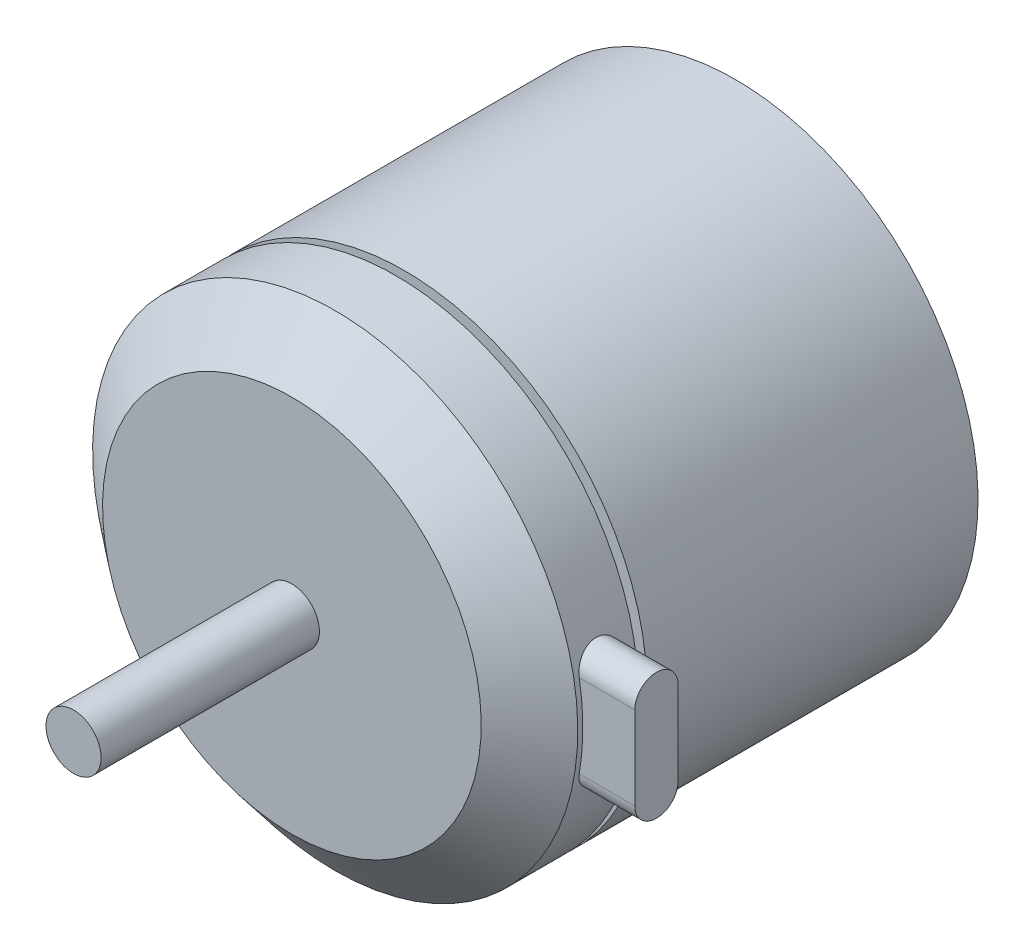
SolidWorks part; units mm, degrees
ref_plane "Front Plane" through (0, 0, 0) normal (0, 0, 1) x (1, 0, 0)
ref_plane "Top Plane" through (0, 0, 0) normal (0, 1, 0) x (1, 0, 0)
ref_plane "Right Plane" through (0, 0, 0) normal (1, 0, 0) x (0, 0, -1)
sketch "Sketch1" plane through (0, 0, 0) normal (1, 0, 0) x (0, 0, -1)
  line L0 (-22.55, 0) -> (-22.55, 1.59)
  line L1 (-22.55, 1.59) -> (-9.95, 1.59)
  line L2 (-9.95, 1.59) -> (-9.95, 10.927)
  line L3 (-7.45, 14) -> (-3.95, 14)
  line L4 (-3.45, 14) -> (15.65, 14)
  line L5 (15.65, 14) -> (21.05, 6.1878)
  line L6 (21.05, 6.1878) -> (21.05, 4)
  line L7 (21.05, 4) -> (21.6527, 4)
  line L8 (22.55, 2.589) -> (22.55, 1.6601)
  line L9 (-3.95, 14) -> (-3.95, 1.59)
  line L10 (-3.95, 1.59) -> (-3.45, 1.59)
  line L11 (-3.45, 1.59) -> (-3.45, 14)
  line L12 (-22.55, 0) -> (22.55, 0) construction
  line L13 (21.6527, 4) -> (22.55, 2.589)
  line L14 (22.55, 1.6601) -> (22.4799, 1.59)
  line L15 (22.4799, 1.59) -> (22.55, 1.5199)
  line L16 (22.55, 1.5199) -> (22.55, 0)
  line L17 (-22.55, 0) -> (22.55, 0)
  line L18 (-9.95, 10.927) -> (-7.45, 14)
  point P20 (0, 0)
  dimension "D1" = 19.1
  dimension "D2" = 31
  dimension "D3" = 3.18
  dimension "D4" = 28
  dimension "D5" = 6
  dimension "D6" = 0.5
  dimension "D7" = 3.18
  dimension "D8" = 45.1
  dimension "D9" = 8
  dimension "D10" = 135
  dimension "D11" = 3.5
  dimension "D12" = 1.5
revolve "Revolve1" add sketch "Sketch1" angle 360 about L12
sketch "Sketch2" plane through (0, 0, 0) normal (1, 0, 0) x (0, 0, -1)
  line L0 (-5.9089, 2.4) -> (-5.9089, -2.4) construction
  line L1 (-4.6589, 2.4) -> (-4.6589, -2.4)
  line L2 (-7.1589, 2.4) -> (-7.1589, -2.4)
  arc A0 (-4.6589, 2.4) -> (-7.1589, 2.4) centre (-5.9089, 2.4) ccw
  arc A1 (-7.1589, -2.4) -> (-4.6589, -2.4) centre (-5.9089, -2.4) ccw
  point P2 (-5.9089, 0)
  dimension "D1" = 4.8
  dimension "D2" = 2.5
extrude "Boss-Extrude1" add sketch "Sketch2" along normal blind 17
